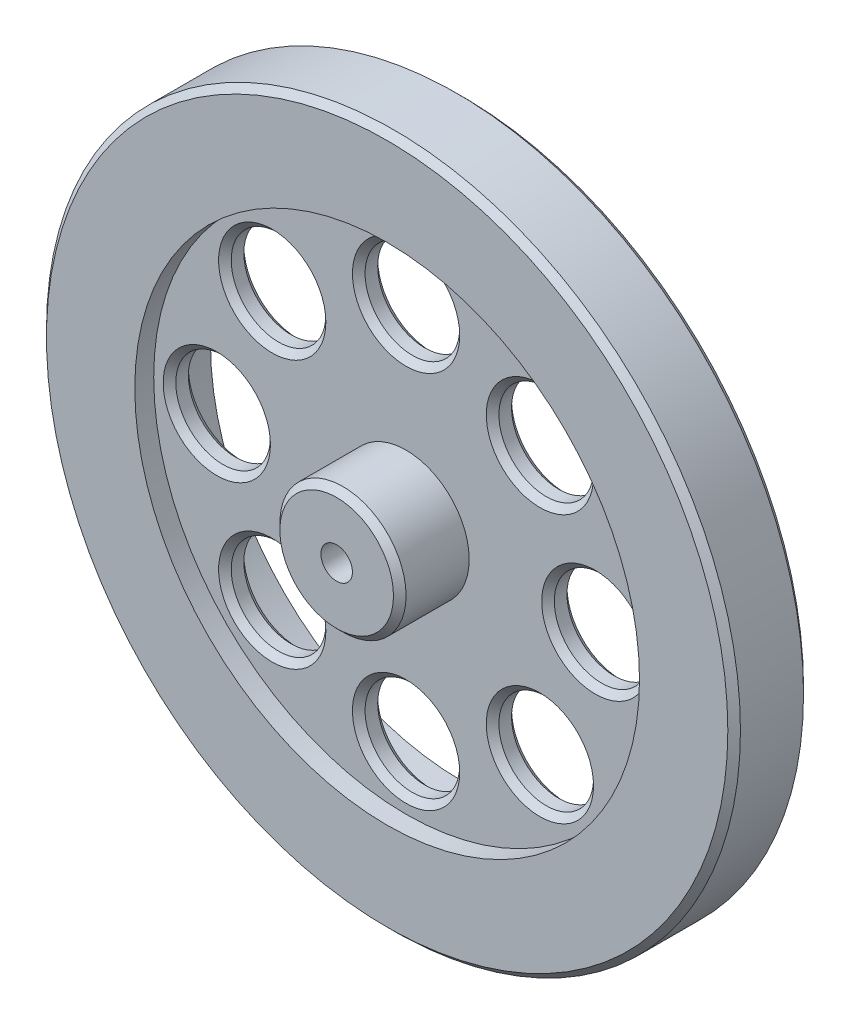
SolidWorks part; units mm, degrees
ref_plane "Front Plane" through (0, 0, 0) normal (0, 0, 1) x (1, 0, 0)
ref_plane "Top Plane" through (0, 0, 0) normal (0, 1, 0) x (1, 0, 0)
ref_plane "Right Plane" through (0, 0, 0) normal (1, 0, 0) x (0, 0, -1)
sketch "Sketch1" plane through (0, 0, 0) normal (0, 0, 1) x (1, 0, 0)
  circle A0 centre (0, 0) radius 55
  dimension "D1" = 110
extrude "Boss-Extrude1" add sketch "Sketch1" along normal blind 12
sketch "Sketch2" plane through (0, 0, 0) normal (0, 0, -1) x (-1, 0, 0)
  circle A0 centre (0, 0) radius 40
  dimension "D1" = 80
extrude "Cut-Extrude1" cut sketch "Sketch2" against normal blind 5
sketch "Sketch3" plane through (0, 0, 12) normal (0, 0, 1) x (1, 0, 0)
  circle A0 centre (0, 0) radius 40
  dimension "D1" = 80
extrude "Cut-Extrude2" cut sketch "Sketch3" against normal blind 3
sketch "Sketch4" plane through (0, 0, 9) normal (0, 0, 1) x (1, 0, 0)
  circle A0 centre (0, 0) radius 10
  dimension "D1" = 20
extrude "Boss-Extrude2" add sketch "Sketch4" along normal blind 11
sketch "Sketch5" plane through (0, 0, 20) normal (0, 0, 1) x (1, 0, 0)
  circle A0 centre (0, 0) radius 2.5
  dimension "D1" = 5
extrude "Cut-Extrude3" cut sketch "Sketch5" against normal through all
sketch "Sketch6" plane through (0, 0, 9) normal (0, 0, 1) x (1, 0, 0)
  circle A0 centre (0, 0) radius 30 construction
  circle A1 centre (0, 30) radius 7.5
  circle A2 centre (21.2132, 21.2132) radius 7.5
  circle A3 centre (30, 0) radius 7.5
  circle A4 centre (21.2132, -21.2132) radius 7.5
  circle A5 centre (0, -30) radius 7.5
  circle A6 centre (-21.2132, -21.2132) radius 7.5
  circle A7 centre (-30, 0) radius 7.5
  circle A8 centre (-21.2132, 21.2132) radius 7.5
  point P21 (0, 0)
  dimension "D1" = 60
  dimension "D2" = 15
  dimension "D3" = 8
extrude "Cut-Extrude4" cut sketch "Sketch6" against normal through all
chamfer "Chamfer1" distance 1 angle 45 2 edges at (55, 0, 12) (55, 0, 0)
